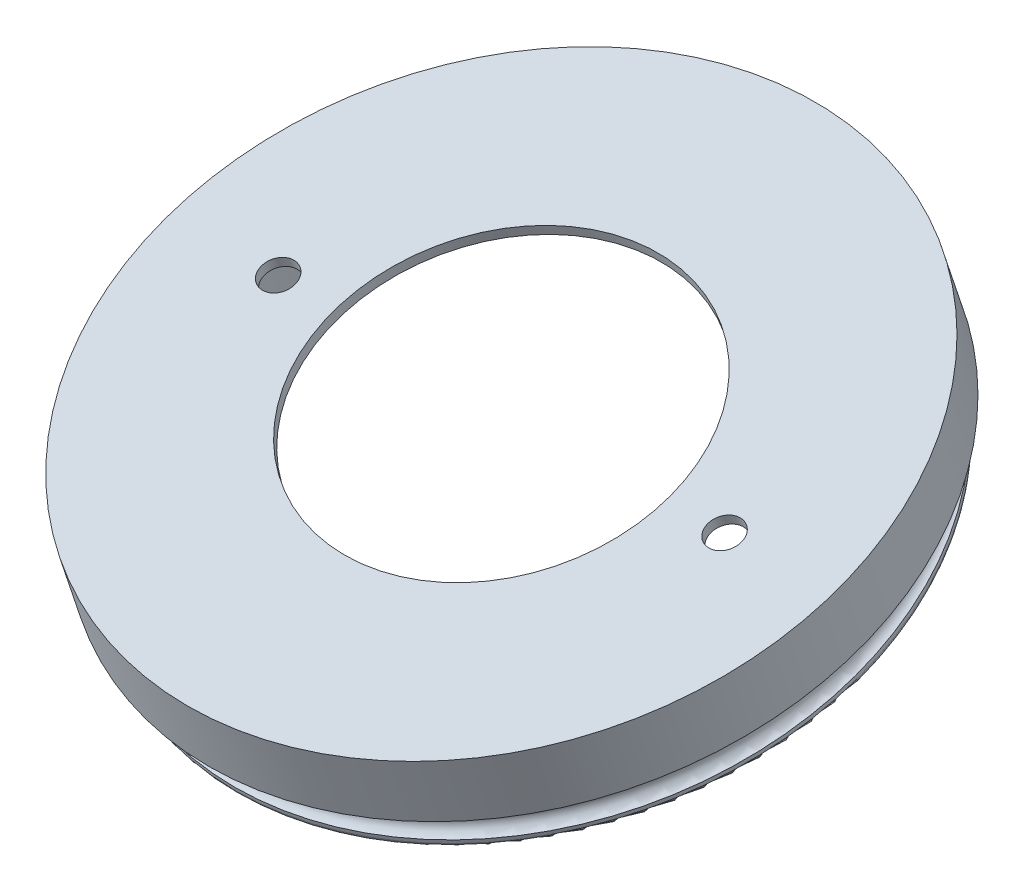
SolidWorks part; units mm, degrees
ref_plane "Plan de face" through (0, 0, 0) normal (0, 0, 1) x (1, 0, 0)
ref_plane "Plan de dessus" through (0, 0, 0) normal (0, 1, 0) x (1, 0, 0)
ref_plane "Plan de droite" through (0, 0, 0) normal (1, 0, 0) x (0, 0, -1)
sketch "Esquisse2" plane through (0, 0, 0) normal (1, 0, 0) x (0, 0, -1)
  line L0 (0, 0) -> (11.8216, -35.3311) construction
  line L1 (51.3932, -33.1332) -> (51.7351, -34.155)
  line L2 (47.7769, -21.1405) -> (49.1046, -20.6962)
  line L3 (49.1046, -20.6962) -> (51.6423, -28.2809)
  line L4 (51.6423, -28.2809) -> (50.4095, -28.6934)
  line L5 (49.3643, -34.9483) -> (46.8258, -27.3617)
  line L8 (50.4095, -28.6934) -> (50.9172, -30.2107)
  line L9 (51.7351, -34.155) -> (49.3643, -34.9483)
  line L10 (46.8258, -27.3617) -> (49.5532, -26.4491)
  line L11 (49.5532, -26.4491) -> (47.7769, -21.1405)
  arc A0 (50.9172, -30.2107) -> (51.3932, -33.1332) centre (51.3932, -31.6332) ccw
  dimension "D5" = 3
  dimension "D2" = 40
  dimension "D3" = 8
  dimension "D4" = 1.3
  dimension "D6" = 2.5
  dimension "D7" = 3.1
  dimension "D8" = 2.5
  dimension "D10" = 1.4
revolve "Révolution2" add sketch "Esquisse2" angle 360 about L0
fillet "Congé3" radius 0.6 1 edges at (0, -54.7701, 22.483)
fillet "Congé4" radius 0.6 1 edges at (0, -58.4124, 20.7625)
sketch "Esquisse4" plane through (0, -33.3884, -11.1716) normal (0, 0.9483, 0.3173) x (1, 0, 0)
  circle A0 centre (0, 0) radius 38.6
  circle A1 centre (0, 0) radius 20
  circle A2 centre (-27, 0) radius 2
  circle A3 centre (27, 0) radius 2
  dimension "D1" = 4
  dimension "D4" = 4
  dimension "D5" = 40
  dimension "D2" = 27
  dimension "D3" = 27
extrude "Boss.-Extru.1" add sketch "Esquisse4" against normal blind 1.2
fillet "Congé5" radius 2 2 edges at (0, -50.9451, 23.6574) (0, -46.7744, 25.0529)
